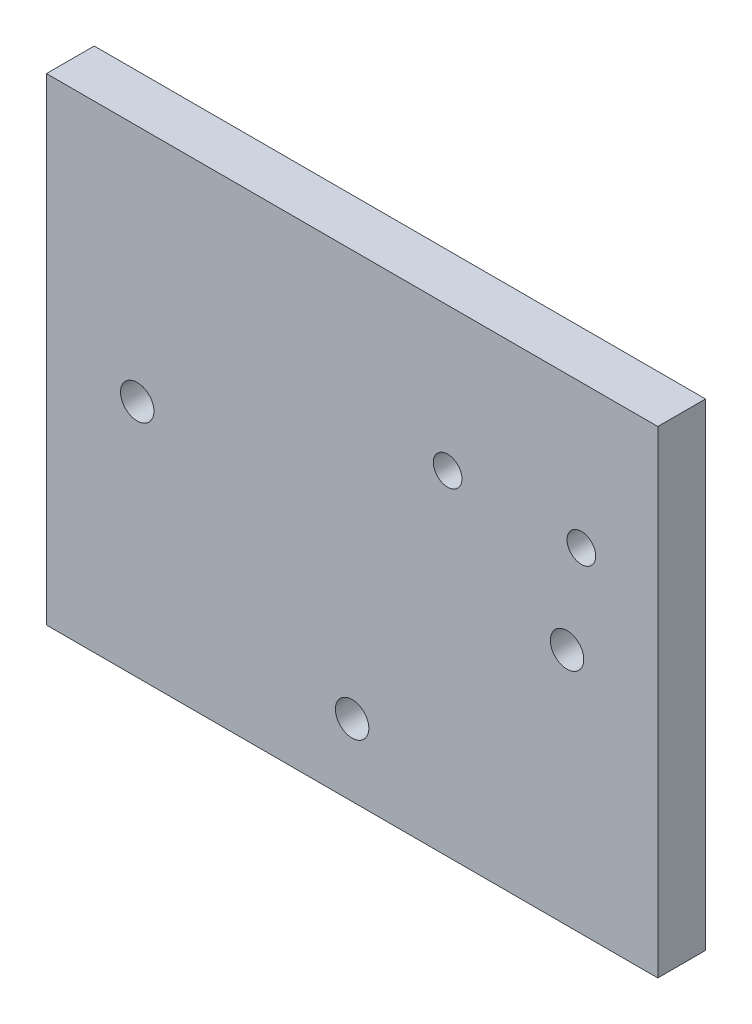
SolidWorks part; units mm, degrees
ref_plane "Front Plane" through (0, 0, 0) normal (0, 0, 1) x (1, 0, 0)
ref_plane "Top Plane" through (0, 0, 0) normal (0, 1, 0) x (1, 0, 0)
ref_plane "Right Plane" through (0, 0, 0) normal (1, 0, 0) x (0, 0, -1)
sketch "Sketch1" plane through (0, 0, 0) normal (0, 0, 1) x (1, 0, 0)
  line L0 (-22.5, 0) -> (22.5, 0) construction
  line L1 (-32, -25) -> (32, -25)
  line L2 (-32, -25) -> (-32, 25)
  line L3 (-32, 25) -> (32, 25)
  line L4 (32, -25) -> (32, 25)
  line L5 (-32, -25) -> (32, 25) construction
  line L6 (-32, 25) -> (32, -25) construction
  line L7 (0, 0) -> (0, -17.5) construction
  line L8 (10, 10) -> (24, 10) construction
  circle A0 centre (-22.5, 0) radius 1.75
  circle A1 centre (22.5, 0) radius 1.75
  circle A2 centre (0, -17.5) radius 1.75
  circle A3 centre (10, 10) radius 1.5
  circle A4 centre (24, 10) radius 1.5
  point P0 (0, 0)
  point P17 (17, 10)
  dimension "D2" = 3.5
  dimension "D7" = 3
  dimension "D1" = 45
  dimension "D3" = 17.5
  dimension "D4" = 50
  dimension "D5" = 64
  dimension "D6" = 14
  dimension "D8" = 15
  dimension "D9" = 10
extrude "Boss-Extrude1" add sketch "Sketch1" along normal blind 5
